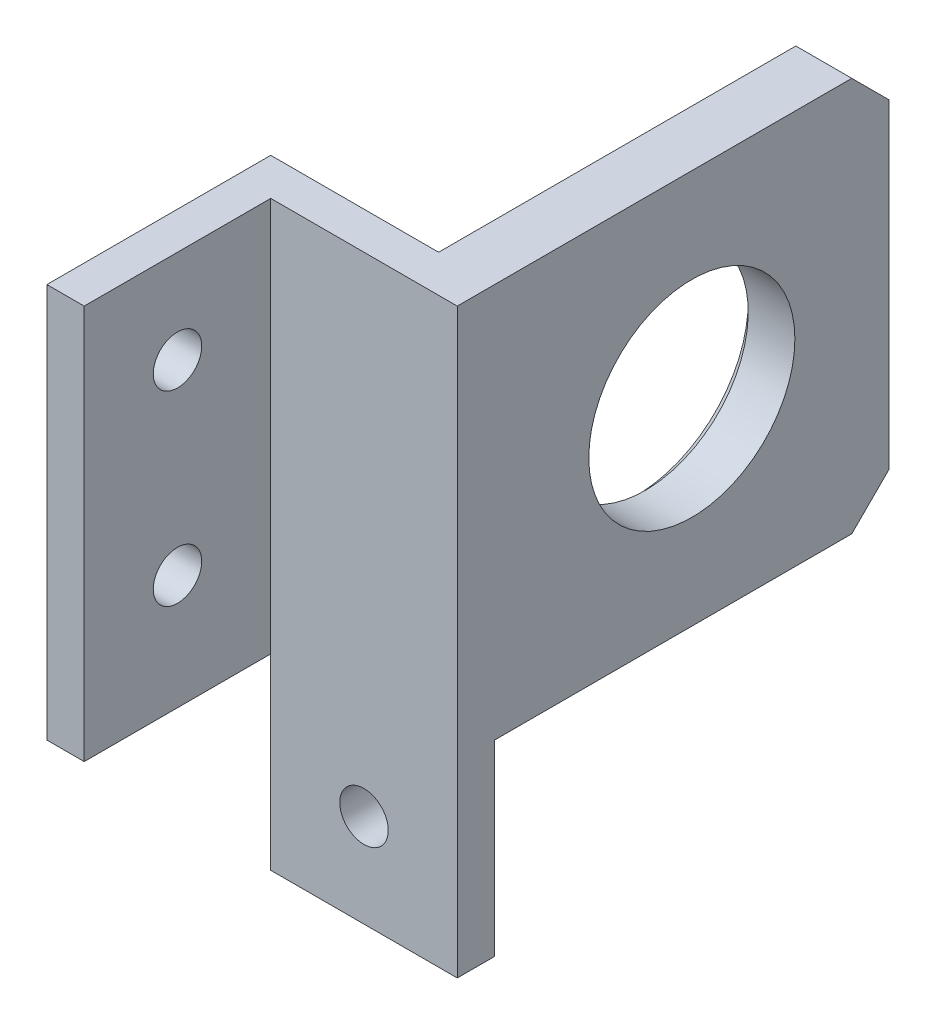
SolidWorks part; units mm, degrees
ref_plane "Přední rovina" through (0, 0, 0) normal (0, 0, 1) x (1, 0, 0)
ref_plane "Horní rovina" through (0, 0, 0) normal (0, 1, 0) x (1, 0, 0)
ref_plane "Pravá rovina" through (0, 0, 0) normal (1, 0, 0) x (0, 0, -1)
sketch "Skica2" plane through (0, 0, 0) normal (0, 0, 1) x (1, 0, 0)
  line L0 (-24.5243, -350) -> (-24.5243, 0) construction
  line L1 (-4.5243, -40) -> (-24.5243, -40)
  line L2 (-4.5243, -40) -> (-4.5243, -82.3)
  line L3 (-4.5243, -82.3) -> (-24.5243, -82.3)
  line L4 (-24.5243, -40) -> (-24.5243, -82.3)
  line L5 (-344.5243, -82.3) -> (-355.5243, -82.3) construction
extrude "Přidat vysunutím1" add sketch "Skica2" along normal blind 4
sketch "Skica3" plane through (-24.5243, 0, 0) normal (-1, 0, 0) x (0, 0, 1)
  line L0 (4, -82.3) -> (0, -82.3) construction
  line L1 (4, -40) -> (-20, -40)
  line L2 (4, -40) -> (4, -82.3)
  line L3 (4, -82.3) -> (-20, -82.3)
  line L4 (-20, -40) -> (-20, -82.3)
  line L5 (-20, -350) -> (-20, 0) construction
extrude "Přidat vysunutím2" add sketch "Skica3" along normal blind 4
sketch "Skica4" plane through (0, 0, 4) normal (0, 0, 1) x (1, 0, 0)
  line L0 (-28.5243, -82.3) -> (-4.5243, -82.3) construction
  line L1 (-10.5243, -40) -> (-4.5243, -40)
  line L2 (-10.5243, -40) -> (-10.5243, -82.3)
  line L3 (-10.5243, -82.3) -> (-4.5243, -82.3)
  line L4 (-4.5243, -40) -> (-4.5243, -82.3)
  line L5 (-4.5243, -82.3) -> (-4.5243, -40) construction
  point P9 (0, 0)
  dimension "D1" = 6
extrude "Přidat vysunutím3" add sketch "Skica4" along normal up to surface (42.3 mm away)
sketch "Skica5" plane through (-4.5243, 0, 0) normal (1, 0, 0) x (0, 0, -1)
  circle A0 centre (-25.15, -61.15) radius 11.05
  dimension "D1" = 22.1
extrude "Odebrat vysunutím1" cut sketch "Skica5" against normal blind 7
sketch "Skica7" plane through (-28.5243, 0, 0) normal (-1, 0, 0) x (0, 0, 1)
  line L0 (-20, -40) -> (-20, -82.3) construction
  line L1 (4, -40) -> (-20, -40) construction
  circle A0 centre (-10, -50) radius 2.6
  circle A1 centre (-10, -70) radius 2.6
  dimension "D3" = 5.2
  dimension "D1" = 10
  dimension "D2" = 10
  dimension "D4" = 2
extrude "Odebrat vysunutím3" cut sketch "Skica7" against normal blind 4
chamfer "Zkosení1" distance 1 angle 45 1 edges at (-10.5243, -50.1, 25.15)
sketch "Skica8" plane through (0, -82.3, 0) normal (0, -1, 0) x (1, 0, 0)
  line L0 (-28.5243, 4) -> (-10.5243, 4) construction
  line L1 (-4.5243, 0) -> (-24.5243, 0)
  line L2 (-4.5243, 0) -> (-4.5243, 4)
  line L3 (-4.5243, 4) -> (-24.5243, 4)
  line L4 (-24.5243, 0) -> (-24.5243, 4)
  point P7 (0, 0)
extrude "Přidat vysunutím4" add sketch "Skica8" along normal up to surface (20.0916 mm away)
sketch "Skica9" plane through (0, 0, 4) normal (0, 0, 1) x (1, 0, 0)
  line L0 (-24.5243, -102.3916) -> (-4.5243, -102.3916) construction
  line L1 (-4.5243, -102.3916) -> (-4.5243, -82.3) construction
  circle A0 centre (-14.5243, -92.3916) radius 2.6
  dimension "D3" = 5.2
  dimension "D1" = 10
  dimension "D2" = 10
extrude "Odebrat vysunutím4" cut sketch "Skica9" against normal blind 4
sketch "Skica10" plane through (-10.5243, 0, 0) normal (-1, 0, 0) x (0, 0, 1)
  line L0 (46.3, -44) -> (42.3, -40)
  line L1 (46.3, -40) -> (46.3, -82.3) construction
  line L2 (42.3, -40) -> (46.3, -44) construction
  line L3 (46.3, -40) -> (4, -40) construction
  line L4 (42.3, -40) -> (46.5659, -39.2593)
  line L5 (46.5659, -39.2593) -> (46.3, -44)
  line L6 (42.3, -82.3) -> (46.3, -78.3)
  line L7 (46.3, -82.3) -> (4, -82.3) construction
  line L8 (46.3, -78.3) -> (42.3, -82.3) construction
  line L9 (46.3, -78.3) -> (47.7456, -80.3)
  line L10 (47.7456, -80.3) -> (46.3, -85.4154)
  line L11 (46.3, -85.4154) -> (42.3, -82.3)
extrude "Odebrat vysunutím5" cut sketch "Skica10" against normal blind 80
mirror "Zrcadlit1" about plane through (-28.5243, -40, -20) normal (0, 0, 1) of bodies 109
sketch "Skica11" plane through (-28.5243, 0, 0) normal (-1, 0, 0) x (0, 0, 1)
  line L1 (-20, -40) -> (64.6922, -40)
  line L2 (-20, -40) -> (-20, -120.4742)
  line L3 (-20, -120.4742) -> (64.6922, -120.4742)
  line L4 (64.6922, -40) -> (64.6922, -120.4742)
extrude "Odebrat vysunutím6" cut sketch "Skica11" against normal up to surface (24 mm away) up to face at (-4.5243, -61.15, 14.1)
